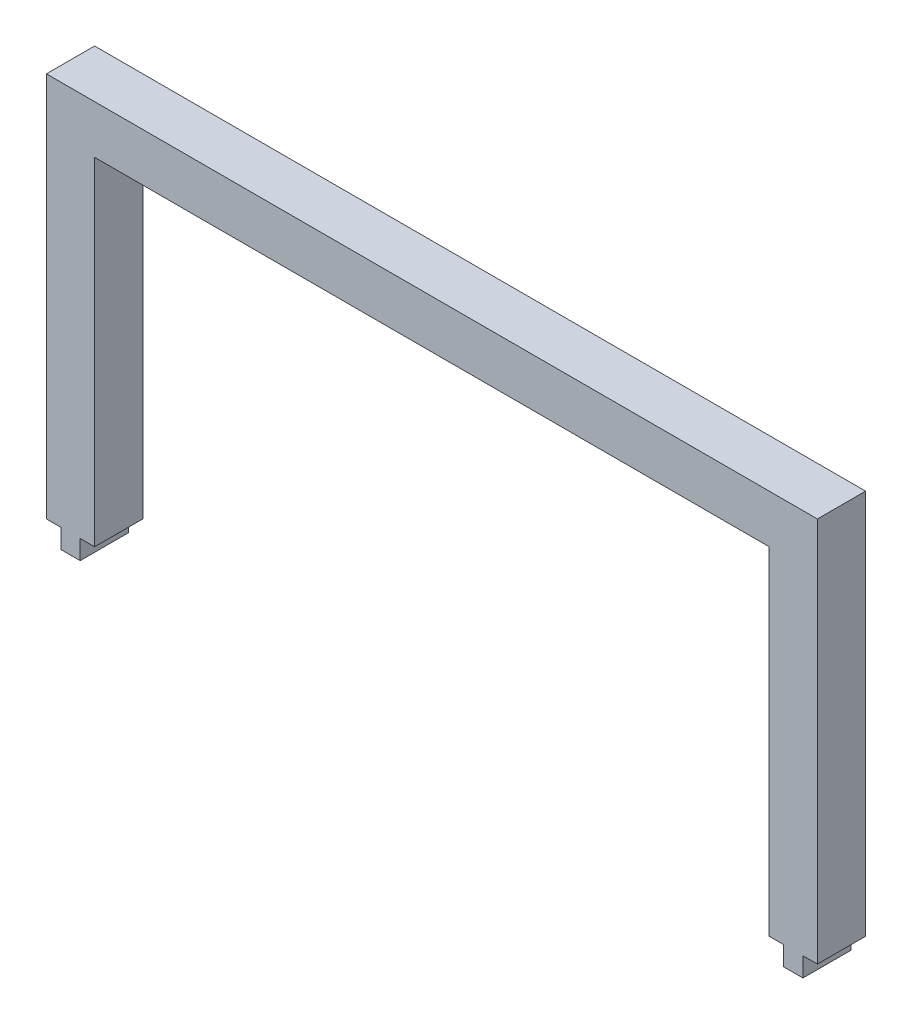
SolidWorks part; units mm, degrees
ref_plane "Front Plane" through (0, 0, 0) normal (0, 0, 1) x (1, 0, 0)
ref_plane "Top Plane" through (0, 0, 0) normal (0, 1, 0) x (1, 0, 0)
ref_plane "Right Plane" through (0, 0, 0) normal (1, 0, 0) x (0, 0, -1)
sketch "Sketch1" plane through (0, 0, 0) normal (0, 0, 1) x (1, 0, 0)
  line L1 (-502.8662, 247.1338) -> (297.1338, 247.1338)
  line L2 (-502.8662, 247.1338) -> (-502.8662, -152.8662)
  line L3 (-502.8662, -152.8662) -> (297.1338, -152.8662)
  line L4 (297.1338, 247.1338) -> (297.1338, -152.8662)
  line L5 (-487.8662, -152.8662) -> (-467.8662, -152.8662)
  line L6 (-487.8662, -152.8662) -> (-487.8662, -172.8662)
  line L7 (-487.8662, -172.8662) -> (-467.8662, -172.8662)
  line L8 (-467.8662, -152.8662) -> (-467.8662, -172.8662)
  line L9 (262.1338, -152.8662) -> (282.1338, -152.8662)
  line L10 (262.1338, -152.8662) -> (262.1338, -172.8662)
  line L11 (262.1338, -172.8662) -> (282.1338, -172.8662)
  line L12 (282.1338, -152.8662) -> (282.1338, -172.8662)
  line L13 (-452.8662, -152.8662) -> (247.1338, -152.8662)
  line L14 (-452.8662, -152.8662) -> (-452.8662, 197.1338)
  line L15 (-452.8662, 197.1338) -> (247.1338, 197.1338)
  line L16 (247.1338, -152.8662) -> (247.1338, 197.1338)
  dimension "D1" = 800
  dimension "D2" = 400
  dimension "D3" = 50
  dimension "D4" = 50
  dimension "D5" = 50
  dimension "D6" = 20
  dimension "D7" = 20
  dimension "D8" = 20
  dimension "D9" = 20
  dimension "D10" = 15
  dimension "D11" = 15
extrude "Boss-Extrude1" add sketch "Sketch1" along normal blind 50 contours L16 L3 L4 L1 L2 L14 L15 | L8 L3 L6 L7 | L12 L3 L10 L11
equation "\"ScannerWidth\"= 800"
equation "\"ScannerHeight\"= 400"
equation "\"ScannerThickness\"= 50"
equation "\"LegWidth\"= 20"
equation "\"LegDepth\"= 20"
equation "\"D1@Sketch1\"=\"ScannerWidth\""
equation "\"D2@Sketch1\"=\"ScannerHeight\""
equation "\"D3@Sketch1\"=\"ScannerThickness\""
equation "\"D4@Sketch1\"=\"ScannerThickness\""
equation "\"D5@Sketch1\"=\"ScannerThickness\""
equation "\"D6@Sketch1\"=\"LegWidth\""
equation "\"D7@Sketch1\"=\"LegDepth\""
equation "\"D8@Sketch1\"=\"LegDepth\""
equation "\"D9@Sketch1\"=\"LegDepth\""
equation "\"D10@Sketch1\"=(\"ScannerThickness\"-\"LegWidth\")/2"
equation "\"D11@Sketch1\"=(\"ScannerThickness\"-\"LegWidth\")/2"
equation "\"ScannerDepth\"= 50"
equation "\"D1@Boss-Extrude1\"=\"ScannerDepth\""
